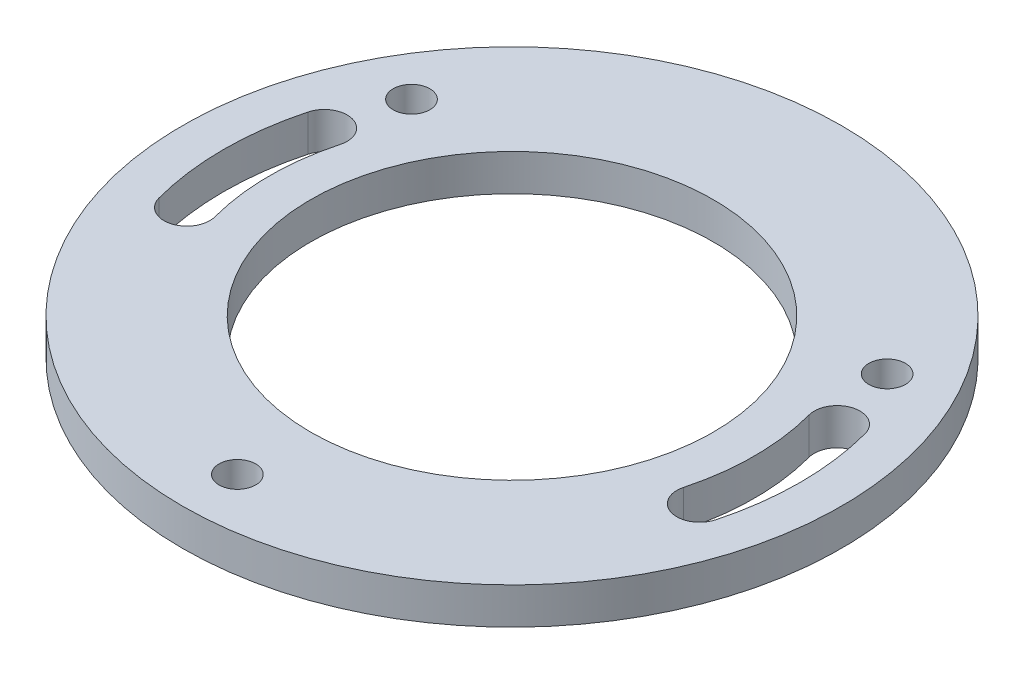
SolidWorks part; units mm, degrees
material "Thornel Mat VMA"
ref_plane "前视基准面" through (0, 0, 0) normal (0, 0, 1) x (1, 0, 0)
ref_plane "上视基准面" through (0, 0, 0) normal (0, 1, 0) x (1, 0, 0)
ref_plane "右视基准面" through (0, 0, 0) normal (1, 0, 0) x (0, 0, -1)
sketch "草图1" plane through (0, 0, 0) normal (0, 1, 0) x (1, 0, 0)
  line L0 (0, -55) -> (0, 55) construction
  circle A1 centre (0, 0) radius 22
  arc A5 (-28.0118, -7.5058) -> (-28.0118, 7.5058) centre (0, 0) cw construction
  arc A6 (-30.4267, 8.1528) -> (-30.4267, -8.1528) centre (0, 0) ccw
  arc A7 (-25.597, 6.8587) -> (-25.597, -6.8587) centre (0, 0) ccw
  arc A8 (-25.597, 6.8587) -> (-30.4267, 8.1528) centre (-28.0118, 7.5058) ccw
  arc A9 (-30.4267, -8.1528) -> (-25.597, -6.8587) centre (-28.0118, -7.5058) ccw
  arc A15 (28.0118, -7.5058) -> (28.0118, 7.5058) centre (0, 0) ccw construction
  arc A46 (30.4267, 8.1528) -> (30.4267, -8.1528) centre (0, 0) cw
  arc A51 (25.597, 6.8587) -> (25.597, -6.8587) centre (0, 0) cw
  circle A56 centre (0, 0) radius 36
  circle A57 centre (0, 0) radius 30 construction
  circle A58 centre (-25.9808, 15) radius 2
  circle A59 centre (25.9808, 15) radius 2
  circle A60 centre (0, -30) radius 2
  arc A61 (25.597, 6.8587) -> (30.4267, 8.1528) centre (28.0118, 7.5058) cw
  arc A62 (30.4267, -8.1528) -> (25.597, -6.8587) centre (28.0118, -7.5058) cw
  point P8 (0, -30)
  point P13 (-29, 0)
  point P19 (29, 0)
  dimension "D1" = 44
  dimension "D2" = 72
  dimension "D3" = 4.5
  dimension "D4" = 2.5
  dimension "D7" = 60
  dimension "D8" = 4
  dimension "D5" = 30
  dimension "D6" = 3
extrude "凸台-拉伸1" add sketch "草图1" along normal blind 4
sketch "草图2" plane through (0, 4, 0) normal (0, 1, 0) x (1, 0, 0)
  line L0 (-55, 0) -> (55, 0) construction
  circle A9 centre (27, 11.3) radius 2.9
  circle A11 centre (-25, 6) radius 2.9
  circle A13 centre (-25, -6) radius 2.9
  circle A14 centre (27, -11.3) radius 2.9
  dimension "D1" = 12
  dimension "D2" = 25
  dimension "D3" = 5.8
  dimension "D4" = 27
  dimension "D5" = 22.6
extrude "切除-拉伸1" [suppressed] cut sketch "草图2" against normal through all
fillet "圆角1" [suppressed] radius 1
